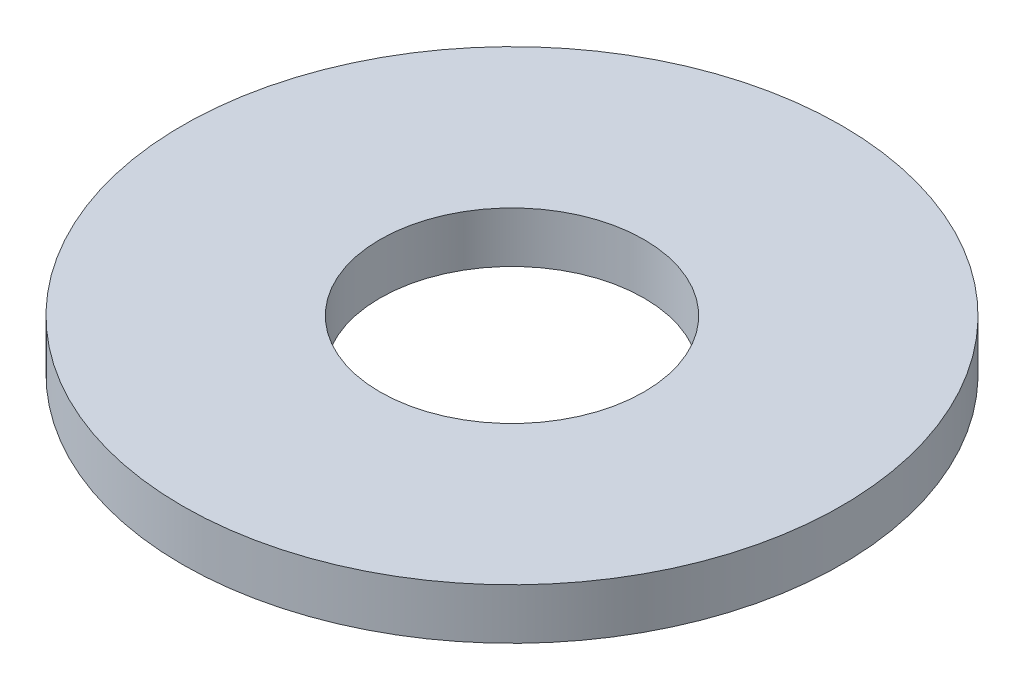
SolidWorks part; units mm, degrees
ref_plane "Front Plane" through (0, 0, 0) normal (0, 0, 1) x (1, 0, 0)
ref_plane "Top Plane" through (0, 0, 0) normal (0, 1, 0) x (1, 0, 0)
ref_plane "Right Plane" through (0, 0, 0) normal (1, 0, 0) x (0, 0, -1)
sketch "Sketch1" plane through (0, 0, 0) normal (0, 1, 0) x (1, 0, 0)
  circle A0 centre (0, 0) radius 1.5875
  circle A1 centre (0, 0) radius 3.9624
  dimension "D1" = 3.175
  dimension "D2" = 7.9248
extrude "Boss-Extrude1" add sketch "Sketch1" along normal blind 0.6096
